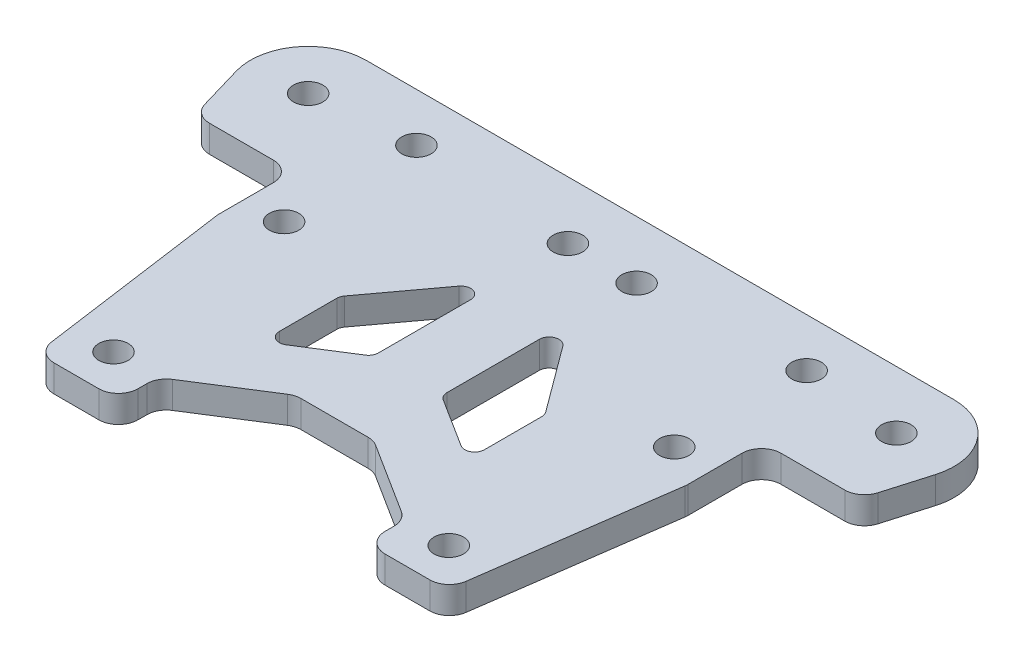
SolidWorks part; units mm, degrees
ref_plane "Plano frontal" through (0, 0, 0) normal (0, 0, 1) x (1, 0, 0)
ref_plane "Plano superior" through (0, 0, 0) normal (0, 1, 0) x (1, 0, 0)
ref_plane "Plano direito" through (0, 0, 0) normal (1, 0, 0) x (0, 0, -1)
sketch "Esboço3" plane through (0, 0, 0) normal (0, 1, 0) x (1, 0, 0)
  line L0 (0, 0) -> (0, 43.9595) construction
  line L1 (-30, 0) -> (30, 0)
  line L2 (35.6566, -7.55) -> (34.321, -12.1119)
  line L3 (32.4016, -13.55) -> (25.9, -13.55)
  line L4 (23.9, -15.55) -> (23.9, -21.0608)
  line L5 (23.8807, -21.3378) -> (21.141, -40.927)
  line L6 (19.1603, -42.65) -> (14.6, -42.65)
  line L7 (12.6, -40.65) -> (12.6, -39.7503)
  line L8 (4.4902, -33.5107) -> (11.6706, -38.061)
  line L9 (3.4196, -33.2) -> (-3.4196, -33.2)
  line L10 (-4.4902, -33.5107) -> (-11.6706, -38.061)
  line L11 (-12.6, -40.65) -> (-12.6, -39.7503)
  line L12 (-19.1603, -42.65) -> (-14.6, -42.65)
  line L13 (-23.8807, -21.3378) -> (-21.141, -40.927)
  line L14 (-23.9, -15.55) -> (-23.9, -21.0608)
  line L15 (-32.4016, -13.55) -> (-25.9, -13.55)
  line L16 (-35.6566, -7.55) -> (-34.321, -12.1119)
  arc A0 (30, 0) -> (35.6566, -7.55) centre (30, -5.894) cw
  arc A1 (4.4902, -33.5107) -> (3.4196, -33.2) centre (3.4196, -35.2) ccw
  arc A2 (12.6, -39.7503) -> (11.6706, -38.061) centre (10.6, -39.7503) ccw
  arc A3 (14.6, -42.65) -> (12.6, -40.65) centre (14.6, -40.65) cw
  arc A4 (21.141, -40.927) -> (19.1603, -42.65) centre (19.1603, -40.65) cw
  arc A5 (23.9, -21.0608) -> (23.8807, -21.3378) centre (21.9, -21.0608) cw
  arc A6 (25.9, -13.55) -> (23.9, -15.55) centre (25.9, -15.55) ccw
  arc A7 (34.321, -12.1119) -> (32.4016, -13.55) centre (32.4016, -11.55) cw
  arc A8 (-34.321, -12.1119) -> (-32.4016, -13.55) centre (-32.4016, -11.55) ccw
  arc A9 (-25.9, -13.55) -> (-23.9, -15.55) centre (-25.9, -15.55) cw
  arc A10 (-23.9, -21.0608) -> (-23.8807, -21.3378) centre (-21.9, -21.0608) ccw
  arc A11 (-21.141, -40.927) -> (-19.1603, -42.65) centre (-19.1603, -40.65) ccw
  arc A12 (-14.6, -42.65) -> (-12.6, -40.65) centre (-14.6, -40.65) ccw
  arc A13 (-12.6, -39.7503) -> (-11.6706, -38.061) centre (-10.6, -39.7503) cw
  arc A14 (-4.4902, -33.5107) -> (-3.4196, -33.2) centre (-3.4196, -35.2) cw
  arc A15 (-30, 0) -> (-35.6566, -7.55) centre (-30, -5.894) ccw
  point P1 (-33.9, -13.55)
  point P2 (12.6, -36.067)
  point P11 (0, 0)
  point P18 (0, 0)
  point P19 (4, -33.2)
  point P22 (12.6, -38.65)
  point P25 (12.6, -42.65)
  point P28 (20.9, -42.65)
  point P31 (23.9, -21.2)
  point P34 (23.9, -13.55)
  point P37 (33.9, -13.55)
  point P62 (0, -33.2)
  point P63 (-23.9, -13.55)
  point P64 (-23.9, -21.2)
  point P65 (-20.9, -42.65)
  point P66 (-12.6, -42.65)
  point P67 (-12.6, -38.65)
  point P68 (-4, -33.2)
  dimension "D13" = 2
  dimension "D6" = 5.894
  dimension "D1" = 30
  dimension "D2" = 42.65
  dimension "D3" = 21.2
  dimension "D4" = 13.55
  dimension "D5" = 12.6
  dimension "D7" = 10
  dimension "D8" = 20.9
  dimension "D9" = 23.9
  dimension "D10" = 9.45
  dimension "D11" = 4
  dimension "D12" = 4
extrude "Ressalto-extrusão1" add sketch "Esboço3" along normal blind 2.75
sketch "Esboço4" plane through (0, 2.75, 0) normal (0, 1, 0) x (1, 0, 0)
  line L0 (14.6, -42.65) -> (19.1603, -42.65) construction
  line L1 (12.6, -39.7503) -> (12.6, -40.65) construction
  line L2 (23.9, -21.0608) -> (23.9, -15.55) construction
  line L3 (30, 0) -> (-30, 0) construction
  line L4 (3.5, -25.2296) -> (3.5, -15.8144)
  line L5 (5.3041, -15.2199) -> (10.2597, -21.9227)
  line L6 (10.4556, -22.5172) -> (10.4556, -28.3701)
  line L7 (8.9203, -29.2148) -> (3.9647, -26.0743)
  line L8 (0, 0) -> (0, -33.2) construction
  line L9 (-3.4196, -33.2) -> (3.4196, -33.2) construction
  line L10 (4.4902, -33.5107) -> (11.6706, -38.061) construction
  line L11 (-8.9203, -29.2148) -> (-3.9647, -26.0743)
  line L12 (-10.4556, -22.5172) -> (-10.4556, -28.3701)
  line L13 (-5.3041, -15.2199) -> (-10.2597, -21.9227)
  line L14 (-3.5, -25.2296) -> (-3.5, -15.8144)
  circle A0 centre (3.5, -5.894) radius 1.5
  circle A1 centre (30, -5.894) radius 1.5
  circle A2 centre (19.9, -4.95) radius 1.5
  circle A3 centre (19.9, -18.45) radius 1.5
  circle A4 centre (17.1, -38.65) radius 1.5
  arc A5 (3.5, -25.2296) -> (3.9647, -26.0743) centre (4.5, -25.2296) ccw
  arc A6 (10.4556, -28.3701) -> (8.9203, -29.2148) centre (9.4556, -28.3701) cw
  arc A7 (10.2597, -21.9227) -> (10.4556, -22.5172) centre (9.4556, -22.5172) cw
  arc A8 (3.5, -15.8144) -> (5.3041, -15.2199) centre (4.5, -15.8144) cw
  circle A9 centre (-3.5, -5.894) radius 1.5
  arc A10 (-3.5, -15.8144) -> (-5.3041, -15.2199) centre (-4.5, -15.8144) ccw
  arc A11 (-10.2597, -21.9227) -> (-10.4556, -22.5172) centre (-9.4556, -22.5172) ccw
  arc A12 (-10.4556, -28.3701) -> (-8.9203, -29.2148) centre (-9.4556, -28.3701) ccw
  arc A13 (-3.5, -25.2296) -> (-3.9647, -26.0743) centre (-4.5, -25.2296) cw
  circle A14 centre (-17.1, -38.65) radius 1.5
  circle A15 centre (-19.9, -18.45) radius 1.5
  circle A16 centre (-19.9, -4.95) radius 1.5
  circle A17 centre (-30, -5.894) radius 1.5
  point P28 (11.9136, -28.407)
  point P31 (3.5, -25.7798)
  point P34 (10.4556, -30.1877)
  point P37 (10.4556, -22.1877)
  point P40 (3.5, -12.7798)
  point P43 (10.4556, -20.5048)
  point P66 (-3.5, -12.7798)
  point P67 (-10.4556, -22.1877)
  point P68 (-10.4556, -30.1877)
  point P69 (-3.5, -25.7798)
  dimension "D1" = 3
  dimension "D11" = 1
  dimension "D2" = 4
  dimension "D3" = 4.5
  dimension "D4" = 4
  dimension "D5" = 4.95
  dimension "D6" = 18.45
  dimension "D7" = 3.5
  dimension "D8" = 11.7
  dimension "D9" = 8
  dimension "D10" = 13
  dimension "D12" = 6
extrude "Corte-extrusão1" cut sketch "Esboço4" against normal through all
